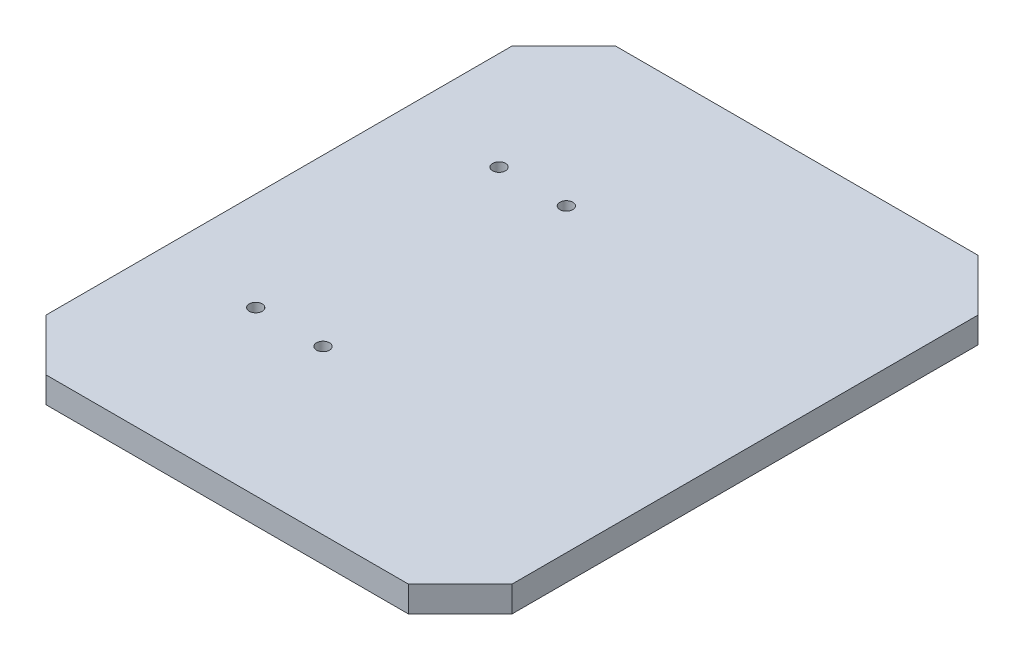
SolidWorks part; units mm, degrees
ref_plane "前视基准面" through (0, 0, 0) normal (0, 0, 1) x (1, 0, 0)
ref_plane "上视基准面" through (0, 0, 0) normal (0, 1, 0) x (1, 0, 0)
ref_plane "右视基准面" through (0, 0, 0) normal (1, 0, 0) x (0, 0, -1)
sketch "草图1" plane through (0, 0, 0) normal (0, 1, 0) x (1, 0, 0)
  line L0 (0, 0) -> (0, 110)
  line L1 (0, 110) -> (90, 110)
  line L2 (90, 110) -> (90, 0)
  line L3 (90, 0) -> (0, 0)
  line L4 (36, 110) -> (36, 0) construction
  line L5 (15, 110) -> (15, 0) construction
  line L6 (0, 55) -> (90, 55) construction
  point P11 (19, 78.5)
  point P12 (32, 78.5)
  point P16 (32, 31.5)
  point P17 (19, 31.5)
  dimension "D1" = 90
  dimension "D2" = 110
  dimension "D3" = 15
  dimension "D4" = 21
  dimension "D5" = 4
  dimension "D6" = 4
  dimension "D7" = 23.5
extrude "凸台-拉伸1" add sketch "草图1" along normal blind 5
chamfer "倒角1" distance 10 distance2 10 4 edges at (0, 2.5, -110) (90, 2.5, -110) (90, 2.5, 0) (0, 2.5, 0)
hole_wizard "M3 螺纹孔1" positions "草图2" profile "草图3" tap size "M3" standard "GB" end condition through all
sketch "草图2" plane through (0, 0, 0) normal (0, -1, 0) x (-1, 0, 0)
  line L1 (-90, 10) -> (-90, 100) construction
  line L2 (-90, 55) -> (0, 55) construction
  line L3 (0, 100) -> (0, 10) construction
  point P0 (-19, 78.5)
  point P2 (-19, 31.5)
  point P4 (-32, 31.5)
  point P6 (-32, 78.5)
  dimension "D1" = 19
  dimension "D2" = 13
  dimension "D3" = 23.5
  dimension "D4" = 23.5
cosmetic thread "孔螺蚊线1" parameters "D2"=3
cosmetic thread "孔螺蚊线2" parameters "D2"=3
cosmetic thread "孔螺蚊线3" parameters "D2"=3
cosmetic thread "孔螺蚊线4" parameters "D2"=3
sketch "草图3" plane through (19, 0, -78.5) normal (1, 0, 0) x (0, 0, -1)
  line L0 (0, 0) -> (0, 5)
  line L1 (0, 5) -> (1.25, 5)
  line L2 (1.25, 5) -> (1.25, 0)
  line L5 (1.25, 0) -> (0, 0)
  line L11 (0, -6.35) -> (0, 107.95) construction
  dimension "通孔螺纹孔钻头直径" = 2.5
  dimension "通孔螺纹孔钻头深度" = 5
